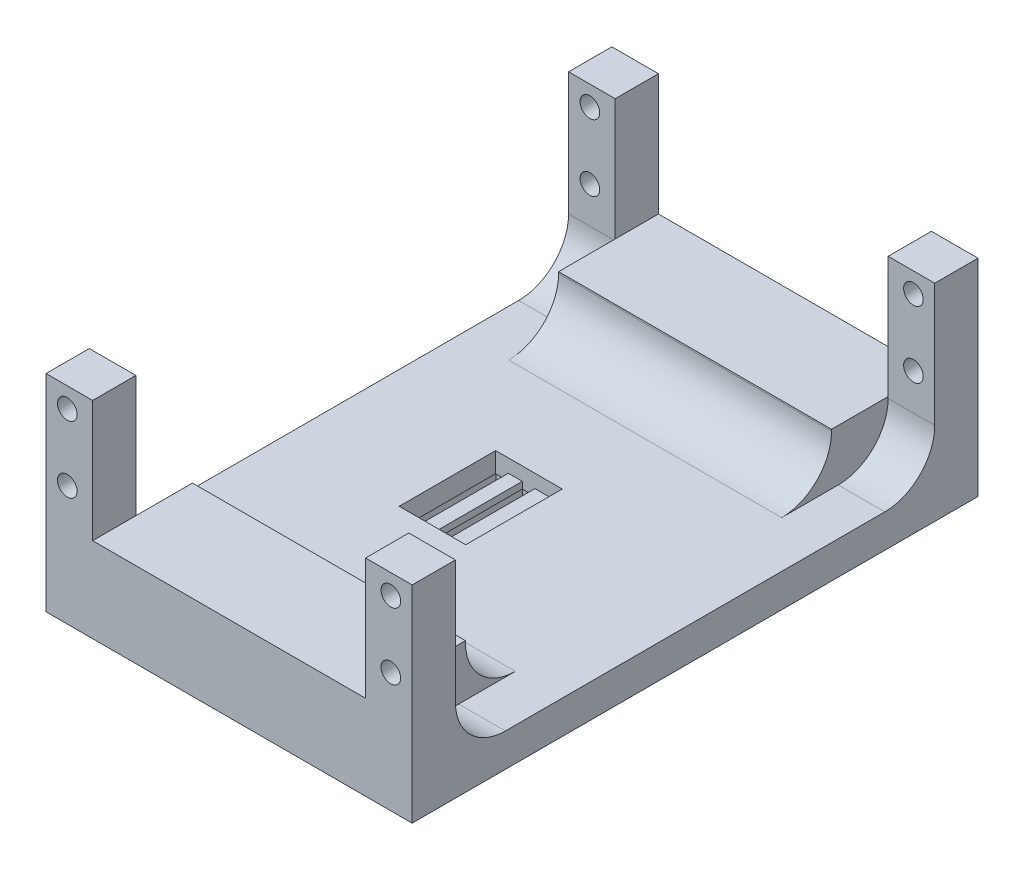
SolidWorks part; units mm, degrees
ref_plane "Спереди" through (0, 0, 0) normal (0, 0, 1) x (1, 0, 0)
ref_plane "Сверху" through (0, 0, 0) normal (0, 1, 0) x (1, 0, 0)
ref_plane "Справа" through (0, 0, 0) normal (1, 0, 0) x (0, 0, -1)
sketch "Эскиз1" plane through (0, 0, 0) normal (0, 1, 0) x (1, 0, 0)
  line L1 (-47.75, 42.5) -> (7.25, 42.5)
  line L2 (-47.75, 42.5) -> (-47.75, -42.5)
  line L3 (-47.75, -42.5) -> (7.25, -42.5)
  line L4 (7.25, 42.5) -> (7.25, -42.5)
  point P4 (7.25, 0)
  dimension "D1" = 55
  dimension "D2" = 85
  dimension "D3" = 7.25
extrude "Бобышка-Вытянуть1" add sketch "Эскиз1" along normal blind 5
sketch "Эскиз2" plane through (0, 5, 0) normal (0, 1, 0) x (1, 0, 0)
  line L0 (-993, 0) -> (49007, 0) construction
  line L1 (-47.75, 42.5) -> (-40.75, 42.5)
  line L2 (-47.75, 42.5) -> (-47.75, 36)
  line L3 (-47.75, 36) -> (-40.75, 36)
  line L4 (-40.75, 42.5) -> (-40.75, 36)
  line L5 (7.25, -42.5) -> (7.25, 42.5) construction
  line L6 (-20.25, -956.862) -> (-20.25, 49043.138) construction
  line L7 (0.25, 42.5) -> (0.25, 36)
  line L8 (7.25, 36) -> (0.25, 36)
  line L9 (7.25, 42.5) -> (7.25, 36)
  line L10 (7.25, 42.5) -> (0.25, 42.5)
  line L11 (7.25, 42.5) -> (-47.75, 42.5) construction
  line L12 (7.25, -42.5) -> (0.25, -42.5)
  line L13 (7.25, -42.5) -> (7.25, -36)
  line L14 (7.25, -36) -> (0.25, -36)
  line L15 (0.25, -42.5) -> (0.25, -36)
  line L16 (-40.75, -42.5) -> (-40.75, -36)
  line L17 (-47.75, -36) -> (-40.75, -36)
  line L18 (-47.75, -42.5) -> (-47.75, -36)
  line L19 (-47.75, -42.5) -> (-40.75, -42.5)
  point P10 (7.25, 0)
  point P16 (-20.25, 42.5)
  point P20 (-20.25, -42.5)
  dimension "D1" = 7
  dimension "D2" = 6.5
extrude "Бобышка-Вытянуть2" add sketch "Эскиз2" along normal blind 26
sketch "Эскиз3" plane through (0, 0, 42.5) normal (0, 0, 1) x (1, 0, 0)
  line L1 (-47.75, 31) -> (-40.75, 31) construction
  line L3 (-20.25, -995) -> (-20.25, 49005) construction
  line L4 (-40.75, 5) -> (0.25, 5) construction
  circle A0 centre (-44.55, 28) radius 1.475
  circle A1 centre (-44.55, 18) radius 1.475
  circle A4 centre (4.05, 18) radius 1.475
  circle A5 centre (4.05, 28) radius 1.475
  point P15 (-20.25, 5)
  dimension "D1" = 10
  dimension "D3" = 2.95
  dimension "D2" = 3
  dimension "D4" = 48.6
extrude "Вырез-Вытянуть1" cut sketch "Эскиз3" against normal through all
sketch "Эскиз4" plane through (0, 5, 0) normal (0, 1, 0) x (1, 0, 0)
  line L0 (0.25, 42.5) -> (0.25, 36) construction
  line L1 (-40.75, 42.5) -> (0.25, 42.5)
  line L2 (-40.75, 42.5) -> (-40.75, 27.5)
  line L3 (-40.75, 27.5) -> (0.25, 27.5)
  line L4 (0.25, 42.5) -> (0.25, 27.5)
  line L5 (-1000, 0) -> (49000, 0) construction
  line L6 (0.25, -42.5) -> (0.25, -27.5)
  line L7 (-40.75, -27.5) -> (0.25, -27.5)
  line L8 (-40.75, -42.5) -> (-40.75, -27.5)
  line L9 (-40.75, -42.5) -> (0.25, -42.5)
  dimension "D1" = 15
extrude "Бобышка-Вытянуть3" add sketch "Эскиз4" along normal blind 7.75
sketch "Эскиз5" plane through (0, 0, 0) normal (0, -1, 0) x (1, 0, 0)
  line L0 (-1071.5513, 0) -> (48928.4487, 0) construction
  line L1 (-20.25, -1025.7217) -> (-20.25, 48974.2783) construction
  line L2 (-8, -24.75) -> (-8, 24.75)
  line L3 (-8, -24.75) -> (-32.5, -24.75)
  line L4 (-32.5, -24.75) -> (-32.5, 24.75)
  line L5 (-8, 24.75) -> (-32.5, 24.75)
  line L6 (-8, -24.75) -> (-32.5, 24.75) construction
  line L7 (-32.5, -24.75) -> (-8, 24.75) construction
  line L8 (-47.75, 42.5) -> (7.25, 42.5) construction
  point P3 (-20.25, 0)
  point P14 (-20.25, 42.5)
  dimension "D1" = 24.5
  dimension "D2" = 49.5
extrude "Бобышка-Вытянуть4" add sketch "Эскиз5" along normal blind 10
sketch "Эскиз7" plane through (0, -10, 0) normal (0, -1, 0) x (1, 0, 0)
  line L0 (-8, -24.75) -> (-8, 24.75) construction
  line L1 (-8, -24.75) -> (-8, 24.75) construction
  line L2 (-8, 24.75) -> (-32.5, 24.75) construction
  line L3 (-32.5, -24.75) -> (-8, -24.75) construction
  circle A0 centre (-13, 20) radius 2.525
  circle A1 centre (-13, -20) radius 2.525
  dimension "D1" = 5
  dimension "D5" = 5.05
  dimension "D2" = 5
  dimension "D3" = 4.75
  dimension "D4" = 4.75
extrude "Вырез-Вытянуть2" cut sketch "Эскиз7" against normal blind 2.25
sketch "Эскиз8" plane through (0, -10, 0) normal (0, -1, 0) x (1, 0, 0)
  line L0 (-1000, 0) -> (49000, 0) construction
  line L13 (-32.5, 24.75) -> (-32.5, -24.75) construction
  line L14 (-30.35, 7.7) -> (-27.65, 7.7)
  line L15 (-30.35, 7.7) -> (-30.35, -7.7)
  line L16 (-30.35, -7.7) -> (-27.65, -7.7)
  line L17 (-27.65, 7.7) -> (-27.65, -7.7)
  line L18 (-26.35, 7.7) -> (-23.65, 7.7)
  line L19 (-26.35, 7.7) -> (-26.35, -7.7)
  line L20 (-26.35, -7.7) -> (-23.65, -7.7)
  line L21 (-23.65, 7.7) -> (-23.65, -7.7)
  point P1 (-23.65, 0)
  dimension "D5" = 2.15
  dimension "D6" = 2.7
  dimension "D7" = 15.4
  dimension "D8" = 4
extrude "Вырез-Вытянуть3" cut sketch "Эскиз8" against normal blind 12
sketch "Эскиз9" plane through (0, 2, 0) normal (0, -1, 0) x (1, 0, 0)
  line L12 (-1030.35, 0) -> (48969.65, 0) construction
  line L13 (-30.35, 7.7) -> (-30.35, -7.7) construction
  line L14 (-29, -992.3) -> (-29, 49007.7) construction
  line L15 (-27.65, 7.7) -> (-30.35, 7.7) construction
  line L16 (-25, -992.3) -> (-25, 49007.7) construction
  line L17 (-23.65, 7.7) -> (-26.35, 7.7) construction
  line L19 (-29.95, -7.25) -> (-28.05, -7.25)
  line L20 (-29.95, -7.25) -> (-29.95, 7.25)
  line L21 (-29.95, 7.25) -> (-28.05, 7.25)
  line L22 (-28.05, -7.25) -> (-28.05, 7.25)
  line L23 (-29.95, -7.25) -> (-28.05, 7.25) construction
  line L24 (-29.95, 7.25) -> (-28.05, -7.25) construction
  line L25 (-25.95, -7.25) -> (-24.05, -7.25)
  line L26 (-25.95, -7.25) -> (-25.95, 7.25)
  line L27 (-25.95, 7.25) -> (-24.05, 7.25)
  line L28 (-24.05, -7.25) -> (-24.05, 7.25)
  line L29 (-25.95, -7.25) -> (-24.05, 7.25) construction
  line L30 (-25.95, 7.25) -> (-24.05, -7.25) construction
  point P15 (-30.35, 0)
  point P20 (-29, 7.7)
  point P21 (-29, 0)
  point P25 (-25, 7.7)
  point P30 (-25, 0)
  dimension "D4" = 1.9
  dimension "D5" = 14.5
extrude "Вырез-Вытянуть4" cut sketch "Эскиз9" against normal blind 1
sketch "Эскиз10" plane through (0, 3, 0) normal (0, -1, 0) x (1, 0, 0)
  line L0 (-29.95, -7.25) -> (-28.05, -7.25) construction
  line L5 (-29.95, 7.25) -> (-19.95, 7.25)
  line L6 (-29.95, 7.25) -> (-29.95, -7.25)
  line L7 (-29.95, -7.25) -> (-19.95, -7.25)
  line L8 (-19.95, 7.25) -> (-19.95, -7.25)
  dimension "D1" = 10
extrude "Вырез-Вытянуть5" cut sketch "Эскиз10" against normal through all
fillet "Скругление1" radius 3 4 edges at (-8, -5, 24.75) (-8, -5, -24.75) (-32.5, -5, -24.75) (-32.5, -5, 24.75)
fillet "Скругление2" radius 7.5 6 edges at (-44.25, 5, -36) (3.75, 5, -36) (-20.25, 5, -27.5) (3.75, 5, 36) (-44.25, 5, 36) (-20.25, 5, 27.5)
